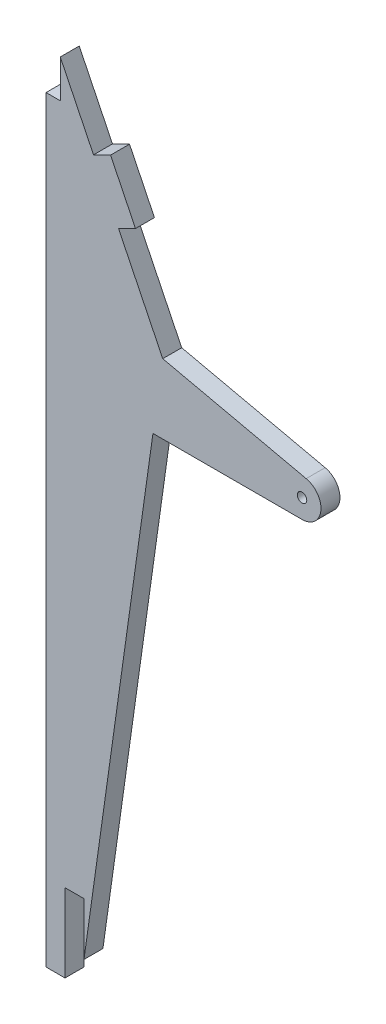
SolidWorks part; units mm, degrees
ref_plane "前视基准面" through (0, 0, 0) normal (0, 0, 1) x (1, 0, 0)
ref_plane "上视基准面" through (0, 0, 0) normal (0, 1, 0) x (1, 0, 0)
ref_plane "右视基准面" through (0, 0, 0) normal (1, 0, 0) x (0, 0, -1)
sketch "草图1" plane through (0, 0, 0) normal (0, 0, 1) x (1, 0, 0)
  line L0 (12.2047, 5.2592) -> (19.4792, 56.9522)
  line L1 (9.7047, 86.4522) -> (9.7047, 82.4522)
  line L2 (9.7047, 82.4522) -> (8.2047, 82.4522)
  line L3 (8.2047, 82.4522) -> (8.2047, 2.5695)
  line L4 (8.2047, 2.5695) -> (10.2047, 2.5695)
  line L5 (10.2047, 2.5695) -> (10.2047, 10.8195)
  line L6 (10.2047, 10.8195) -> (12.2047, 10.8195)
  line L7 (12.2047, 10.8195) -> (12.2047, 5.2592)
  line L8 (13.2116, 79.2619) -> (15.0092, 80.1386)
  line L9 (15.0092, 80.1386) -> (17.6395, 74.7458)
  line L10 (17.6395, 74.7458) -> (15.8419, 73.8691)
  line L11 (20.5123, 64.2933) -> (15.8419, 73.8691)
  line L12 (13.2116, 79.2619) -> (9.7047, 86.4522)
  line L13 (20.5123, 64.2933) -> (35.6419, 60.9038)
  line L14 (35.2047, 56.9522) -> (19.4792, 56.9522)
  circle A0 centre (35.2047, 58.9522) radius 0.5
  arc A1 (35.2047, 56.9522) -> (35.2047, 60.9522) centre (35.2047, 58.9522) ccw
extrude "凸台-拉伸1" add sketch "草图1" along normal blind 2
